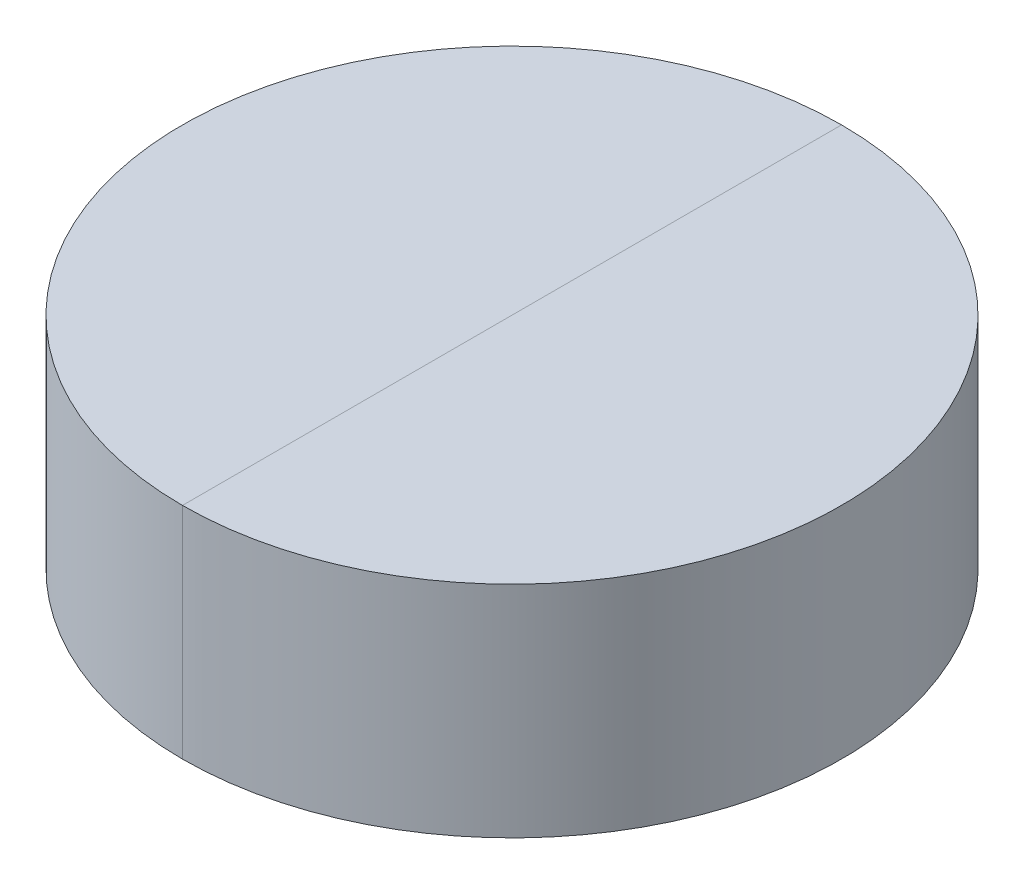
SolidWorks part; units mm, degrees
ref_plane "Plan de face" through (0, 0, 0) normal (0, 0, 1) x (1, 0, 0)
ref_plane "Plan de dessus" through (0, 0, 0) normal (0, 1, 0) x (1, 0, 0)
ref_plane "Plan de droite" through (0, 0, 0) normal (1, 0, 0) x (0, 0, -1)
sketch "Esquisse1" plane through (0, 0, 0) normal (0, 1, 0) x (1, 0, 0)
  line L0 (0, 3) -> (0, -3)
  arc A0 (0, 3) -> (0, -3) centre (0, 0) ccw
  dimension "D1" = 6
extrude "Boss.-Extru.1" add sketch "Esquisse1" along normal blind 2
sketch "Esquisse2" plane through (0, 0, 0) normal (0, 1, 0) x (1, 0, 0)
  line L0 (0, -3) -> (0, 3)
  arc A0 (0, -3) -> (0, 3) centre (0, 0) ccw
extrude "Boss.-Extru.2" add sketch "Esquisse2" along normal up to surface (2 mm away) separate body up to face at (-1.5, 2, 0)
